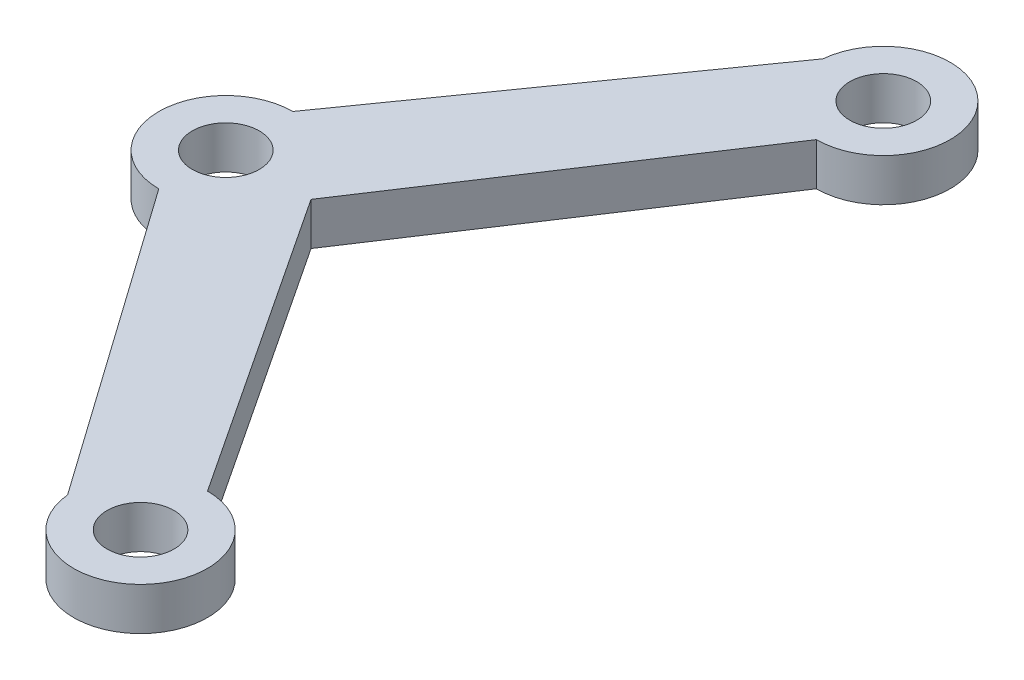
SolidWorks part; units mm, degrees
ref_plane "Front Plane" through (0, 0, 0) normal (0, 0, 1) x (1, 0, 0)
ref_plane "Top Plane" through (0, 0, 0) normal (0, 1, 0) x (1, 0, 0)
ref_plane "Right Plane" through (0, 0, 0) normal (1, 0, 0) x (0, 0, -1)
sketch "Sketch1" plane through (0, 0, 0) normal (0, 1, 0) x (1, 0, 0)
  line L1 (-15.25, -15.25) -> (15.25, -15.25) construction
  line L2 (-15.25, -15.25) -> (-15.25, 15.25) construction
  line L3 (-15.25, 15.25) -> (15.25, 15.25) construction
  line L4 (15.25, -15.25) -> (15.25, 15.25) construction
  line L5 (-15.25, -15.25) -> (15.25, 15.25) construction
  line L6 (-15.25, 15.25) -> (15.25, -15.25) construction
  point P0 (0, 0)
  dimension "D1" = 30.5
sketch "Sketch2" plane through (0, 0, 0) normal (0, 1, 0) x (1, 0, 0)
  line L1 (-23, -16) -> (23, -16) construction
  line L2 (-23, -16) -> (-23, 16) construction
  line L3 (-23, 16) -> (23, 16) construction
  line L4 (23, -16) -> (23, 16) construction
  line L5 (-23, -16) -> (23, 16) construction
  line L6 (-23, 16) -> (23, -16) construction
  line L7 (-23, 0) -> (23, 0) construction
  line L9 (-27, -2.75) -> (-17.9878, -15.509)
  line L10 (-15.25, -12.5) -> (-23.5, 0)
  line L11 (-15.25, 12.5) -> (-23.5, 0)
  line L12 (-17.9878, 15.509) -> (-27, 2.75)
  arc A0 (-27, 2.75) -> (-27, -2.75) centre (-27, 0) ccw
  circle A1 centre (-27, 0) radius 1.375
  circle A2 centre (-15.25, 15.25) radius 1.375
  arc A3 (-15.25, 12.5) -> (-17.9878, 15.509) centre (-15.25, 15.25) ccw
  circle A4 centre (-15.25, -15.25) radius 1.375
  arc A5 (-17.9878, -15.509) -> (-15.25, -12.5) centre (-15.25, -15.25) ccw
  point P0 (0, 0)
  dimension "D4" = 5.5
  dimension "D5" = 2.75
  dimension "D6" = 2.75
  dimension "D7" = 5.5
  dimension "D1" = 32
  dimension "D2" = 46
  dimension "D3" = 4
  dimension "D8" = 3.5
  dimension "D9" = 15.6209
extrude "Boss-Extrude1" add sketch "Sketch2" along normal blind 1.75
sketch "Sketch3" plane through (0, 1.75, 0) normal (0, 1, 0) x (1, 0, 0)
  circle A0 centre (-15.25, 15.25) radius 1.375
  circle A1 centre (-15.25, 15.25) radius 2.75
  circle A2 centre (-15.25, -15.25) radius 2.75
  circle A3 centre (-15.25, -15.25) radius 1.375
  dimension "D1" = 2.75
  dimension "D2" = 5.5
